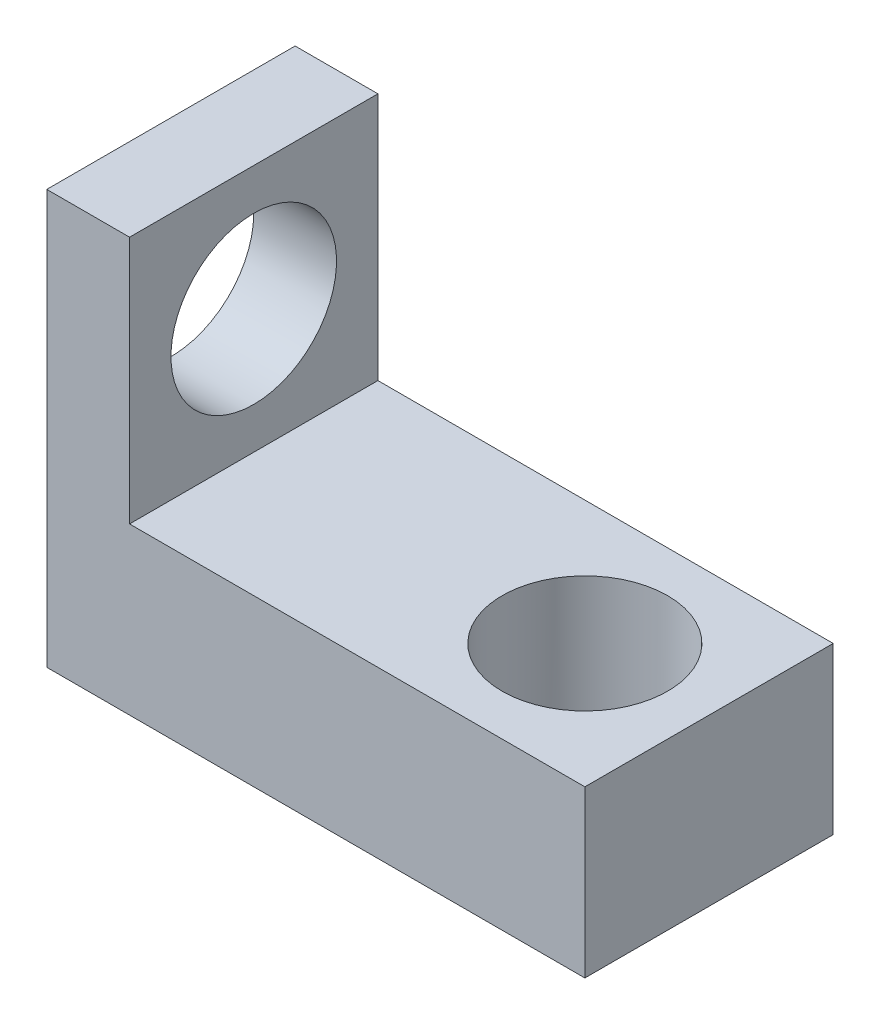
SolidWorks part; units mm, degrees
material "POM Acetal Copolymer"
ref_plane "Front Plane" through (0, 0, 0) normal (0, 0, 1) x (1, 0, 0)
ref_plane "Top Plane" through (0, 0, 0) normal (0, 1, 0) x (1, 0, 0)
ref_plane "Right Plane" through (0, 0, 0) normal (1, 0, 0) x (0, 0, -1)
sketch "Sketch5" plane through (0, 0, 0) normal (0, 0, 1) x (1, 0, 0)
  line L0 (0, 0) -> (0, 50)
  line L1 (0, 50) -> (10, 50)
  line L2 (10, 50) -> (10, 20)
  line L3 (10, 20) -> (65, 20)
  line L4 (65, 20) -> (65, 0)
  line L5 (65, 0) -> (0, 0)
  dimension "D1" = 20
  dimension "D2" = 65
  dimension "D3" = 10
  dimension "D4" = 30
extrude "Boss-Extrude3" add sketch "Sketch5" against normal blind 30 contours L5 L0 L1 L2 L3 L4
sketch "Sketch6" plane through (0, 20, 0) normal (0, 1, 0) x (1, 0, 0)
  line L0 (65, 30) -> (65, 0) construction
  line L1 (10, 30) -> (65, 30) construction
  circle A0 centre (50, 15) radius 10
  dimension "D1" = 20
  dimension "D2" = 15
  dimension "D3" = 15
extrude "Cut-Extrude2" cut sketch "Sketch6" against normal blind 30
cosmetic thread "Cosmetic Thread2"
sketch "Sketch7" plane through (10, 0, 0) normal (1, 0, 0) x (0, 0, -1)
  line L0 (30, 50) -> (0, 50) construction
  line L1 (0, 50) -> (0, 20) construction
  circle A0 centre (15, 35) radius 10
  dimension "D1" = 20
  dimension "D3" = 15
  dimension "D2" = 15
extrude "Cut-Extrude3" cut sketch "Sketch7" against normal blind 30
cosmetic thread "Cosmetic Thread1" parameters "D2"=21
